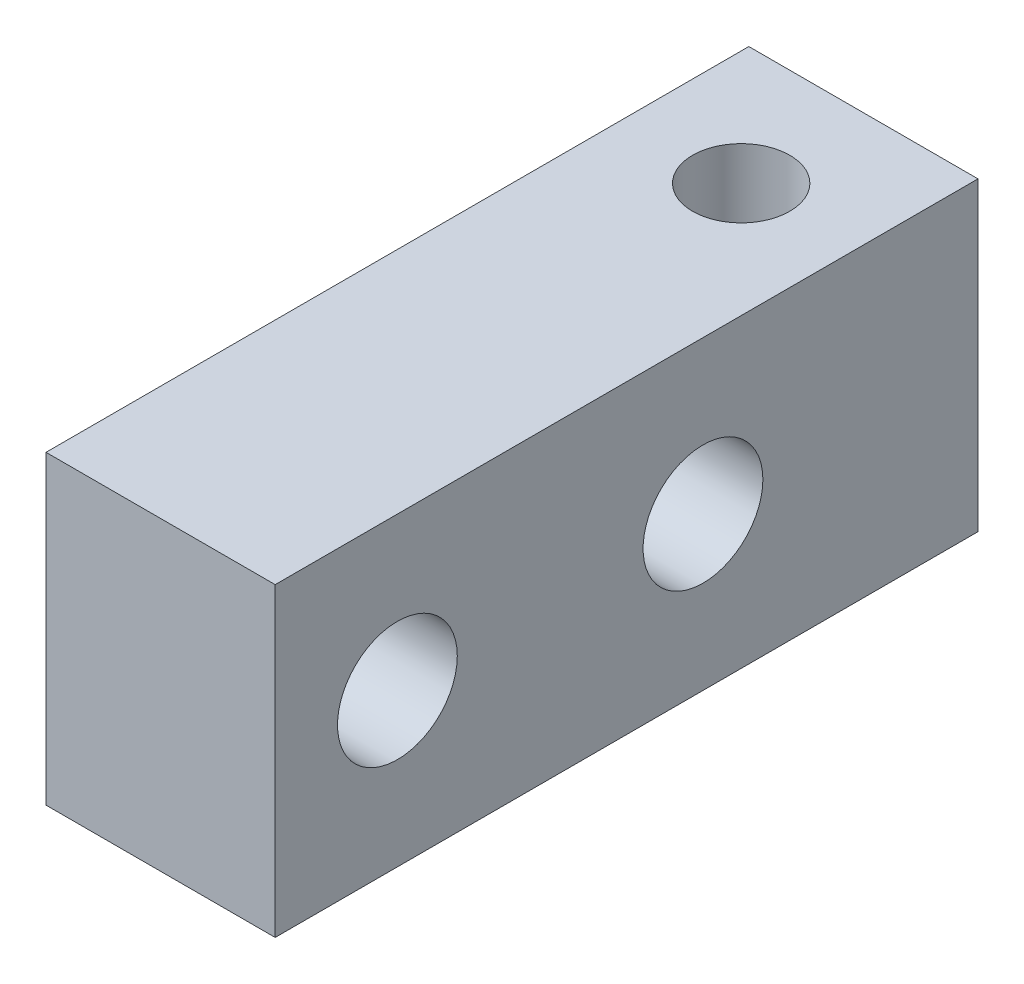
SolidWorks part; units mm, degrees
material "6061-T6 (SS)"
ref_plane "Front Plane" through (0, 0, 0) normal (0, 0, 1) x (1, 0, 0)
ref_plane "Top Plane" through (0, 0, 0) normal (0, 1, 0) x (1, 0, 0)
ref_plane "Right Plane" through (0, 0, 0) normal (1, 0, 0) x (0, 0, -1)
sketch "Sketch1" plane through (0, 0, 0) normal (1, 0, 0) x (0, 0, -1)
  line L0 (5.08, -6.35) -> (5.08, 6.35)
  line L1 (5.08, -6.35) -> (-24.13, -6.35)
  line L2 (5.08, 6.35) -> (-24.13, 6.35)
  line L3 (-24.13, -6.35) -> (-24.13, 6.35)
  line L4 (0, 6.35) -> (0, -6.35) construction
  dimension "D1" = 5.08
  dimension "D2" = 12.7
  dimension "D3" = 29.21
extrude "Boss-Extrude1" add sketch "Sketch1" along normal mid plane 9.525
hole_wizard "#10-32 Tapped Hole1" positions "Sketch2" profile "Sketch3" tap size "#10-32" standard "ANSI Inch" end condition through all
sketch "Sketch2" plane through (0, 6.35, 0) normal (0, 1, 0) x (1, 0, 0)
  point P0 (0, 0)
sketch "Sketch3" plane through (0, 6.35, 0) normal (1, 0, 0) x (0, 0, 1)
  line L0 (0, 0) -> (0, 12.7)
  line L1 (0, 12.7) -> (2.0193, 12.7)
  line L2 (2.0193, 12.7) -> (2.0193, 0)
  line L5 (2.0193, 0) -> (0, 0)
  line L11 (0, -6.35) -> (0, 107.95) construction
  dimension "Thru Tap Drill Dia." = 4.0386
  dimension "Thru Tap Drill Depth" = 12.7
cosmetic thread "Hole Thread1"
hole_wizard "#10 Clearance Hole1" positions "Sketch4" profile "Sketch5" hole size "#10" standard "ANSI Inch" end condition through all
sketch "Sketch4" plane through (4.7625, 0, 0) normal (1, 0, 0) x (0, 0, -1)
  line L0 (-24.13, 0) -> (-19.05, 0) construction
  line L1 (-24.13, 6.35) -> (-24.13, -6.35) construction
  line L2 (-19.05, 0) -> (-6.35, 0) construction
  point P0 (-6.35, 0)
  point P2 (-19.05, 0)
  dimension "D1" = 5.08
  dimension "D2" = 6.35
sketch "Sketch5" plane through (4.7625, 0, 6.35) normal (0, 1, 0) x (0, 0, -1)
  line L0 (0, 0) -> (0, 9.525)
  line L1 (0, 9.525) -> (2.4892, 9.525)
  line L2 (2.4892, 9.525) -> (2.4892, 0)
  line L5 (2.4892, 0) -> (0, 0)
  line L11 (0, -6.35) -> (0, 107.95) construction
  dimension "Thru Hole Dia." = 4.9784
  dimension "Thru Hole Depth" = 9.525
